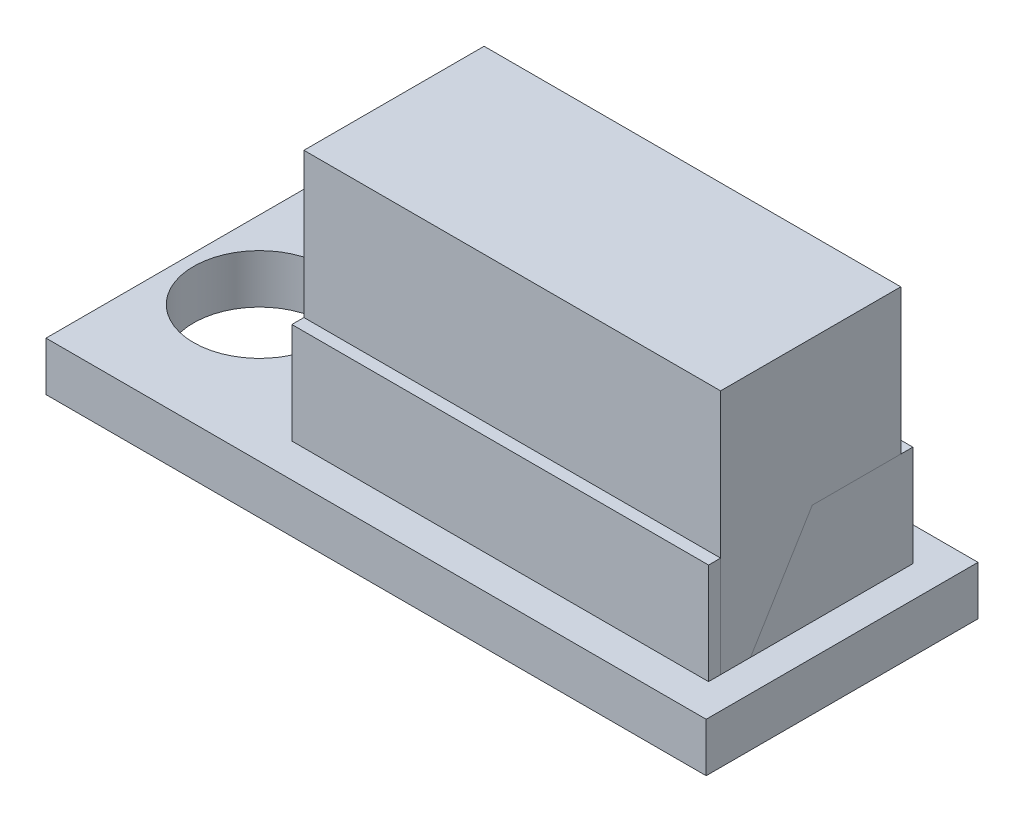
SolidWorks part; units mm, degrees
ref_plane "Front Plane" through (0, 0, 0) normal (0, 0, 1) x (1, 0, 0)
ref_plane "Top Plane" through (0, 0, 0) normal (0, 1, 0) x (1, 0, 0)
ref_plane "Right Plane" through (0, 0, 0) normal (1, 0, 0) x (0, 0, -1)
sketch "Sketch1" plane through (0, 0, 0) normal (0, 1, 0) x (1, 0, 0)
  line L0 (-51.695, -20.5365) -> (-30.105, -20.5365) construction
  line L1 (-51.695, -16.0915) -> (-30.105, -16.0915)
  line L2 (-51.695, -16.0915) -> (-51.695, -24.9815)
  line L3 (-51.695, -24.9815) -> (-30.105, -24.9815)
  line L4 (-30.105, -16.0915) -> (-30.105, -24.9815)
  circle A0 centre (-49.155, -20.5365) radius 2.159
  dimension "D3" = 19.05
  dimension "D1" = 21.59
  dimension "D2" = 8.89
extrude "Boss-Extrude1" add sketch "Sketch1" along normal blind 1.6002
sketch "Sketch2" plane through (0, 0, 0) normal (0, 1, 0) x (1, 0, 0)
  line L0 (-30.105, -16.0915) -> (-51.695, -16.0915) construction
  line L1 (-31.1315, -17.1964) -> (-44.7586, -17.1964)
  line L2 (-31.1315, -17.1964) -> (-31.1315, -23.8766)
  line L3 (-31.1315, -23.8766) -> (-44.7586, -23.8766)
  line L4 (-44.7586, -17.1964) -> (-44.7586, -23.8766)
  line L5 (-51.695, -24.9815) -> (-30.105, -24.9815) construction
  dimension "D1" = 1.1049
  dimension "D2" = 1.1049
  dimension "D3" = 13.6271
extrude "Boss-Extrude2" add sketch "Sketch2" along normal blind 4.9022
sketch "Sketch3" plane through (0, 0, 0) normal (0, 1, 0) x (1, 0, 0)
  line L0 (-44.7586, -17.1964) -> (-44.7586, -23.8766) construction
  line L1 (-44.7586, -17.5901) -> (-31.1315, -17.5901)
  line L2 (-44.7586, -17.5901) -> (-44.7586, -23.4829)
  line L3 (-44.7586, -23.4829) -> (-31.1315, -23.4829)
  line L4 (-31.1315, -17.5901) -> (-31.1315, -23.4829)
  line L5 (-31.1315, -23.8766) -> (-31.1315, -17.1964) construction
  line L6 (-31.1315, -17.1964) -> (-44.7586, -17.1964) construction
  line L7 (-44.7586, -23.8766) -> (-31.1315, -23.8766) construction
  dimension "D1" = 0.3937
  dimension "D2" = 0.3937
extrude "Boss-Extrude3" add sketch "Sketch3" along normal blind 9.6393 separate body
